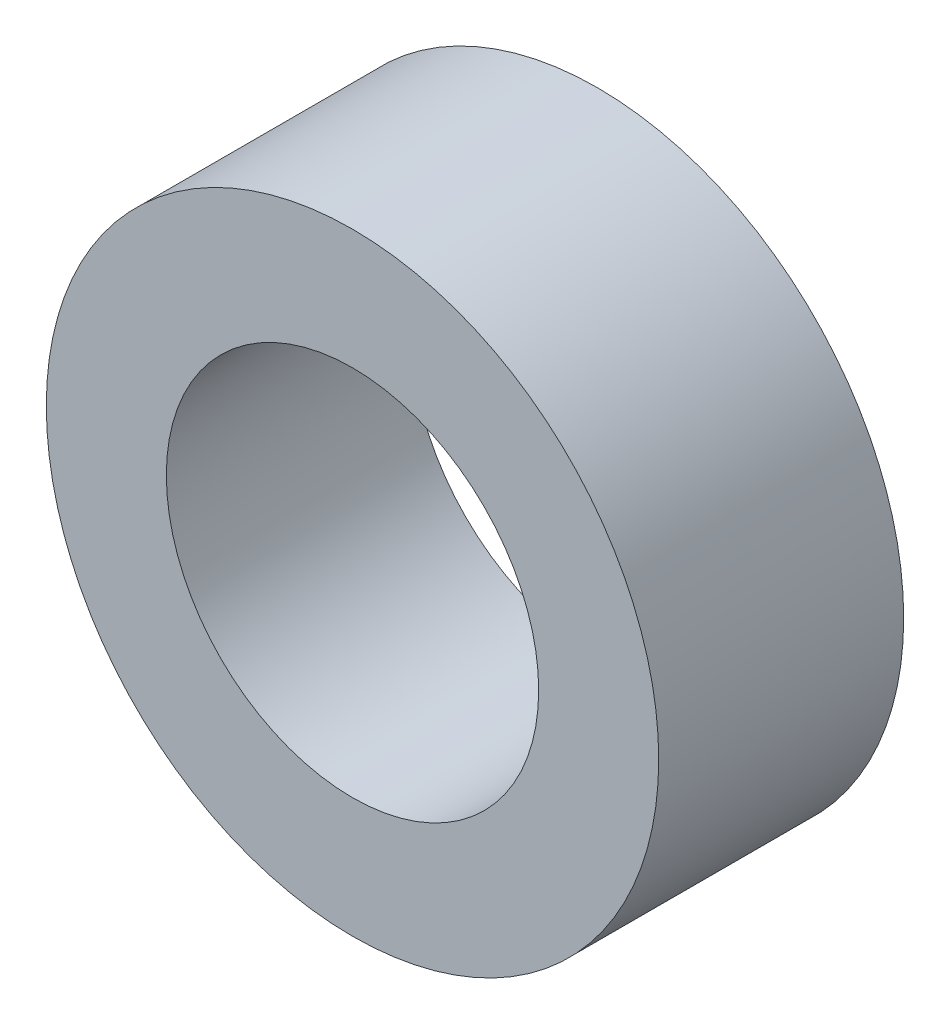
SolidWorks part; units mm, degrees
ref_plane "Front Plane" through (0, 0, 0) normal (0, 0, 1) x (1, 0, 0)
ref_plane "Top Plane" through (0, 0, 0) normal (0, 1, 0) x (1, 0, 0)
ref_plane "Right Plane" through (0, 0, 0) normal (1, 0, 0) x (0, 0, -1)
sketch "Sketch1" plane through (0, 0, 0) normal (0, 0, 1) x (1, 0, 0)
  circle A0 centre (0, 0) radius 7.9375 construction
  circle A1 centre (0, 0) radius 4.826 construction
  point P4 (0, 7.9375)
  dimension "ID" = 9.652
  dimension "OD" = 15.875
sketch "Sketch2" plane through (0, 0, 0) normal (1, 0, 0) x (0, 0, -1)
  line L0 (-152.4, 7.9375) -> (152.4, 7.9375) construction
  point P2 (132.5563, 7.9375)
  point P3 (-132.5563, 7.9375)
  dimension "Length" = 304.8
  dimension "D1" = 19.8438
  dimension "D2" = 19.8438
sketch "Sketch3" plane through (0, 0, 0) normal (0, 0, 1) x (1, 0, 0)
  circle A0 centre (0, 0) radius 4.826 construction
  circle A1 centre (0, 0) radius 7.9375 construction
  circle A2 centre (0, 0) radius 4.826
  circle A3 centre (0, 0) radius 7.9375
extrude "Boss-Extrude1" add sketch "Sketch3" against normal up to vertex (152.4 mm away) and the other way up to vertex (152.4 mm away) up to point (0, 7.9375, -152.4) other way up to point (0, 7.9375, 152.4)
sketch "Sketch4" plane through (0, 0, 152.4) normal (0, 0, 1) x (1, 0, 0)
  circle A0 centre (0, 0) radius 7.9375
extrude "Cut-Extrude1" cut sketch "Sketch4" against normal blind 298.45
equation "\"D1@Sketch2\"=\"OD@Sketch1\"*1.25"
equation "\"D2@Sketch2\"=\"D1@Sketch2\""
